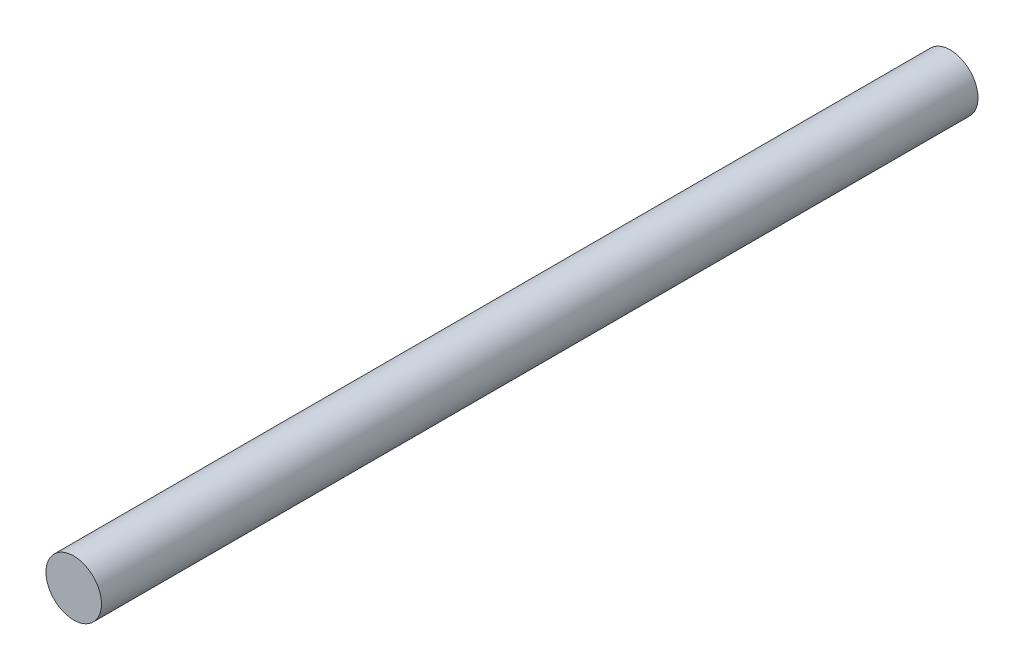
SolidWorks part; units mm, degrees
ref_plane "前视基准面" through (0, 0, 0) normal (0, 0, 1) x (1, 0, 0)
ref_plane "上视基准面" through (0, 0, 0) normal (0, 1, 0) x (1, 0, 0)
ref_plane "右视基准面" through (0, 0, 0) normal (1, 0, 0) x (0, 0, -1)
sketch "草图1" plane through (0, 0, 0) normal (0, 0, 1) x (1, 0, 0)
  circle A0 centre (0, 0) radius 1.9
  dimension "D1" = 3.8
extrude "凸台-拉伸1" add sketch "草图1" along normal mid plane 60
